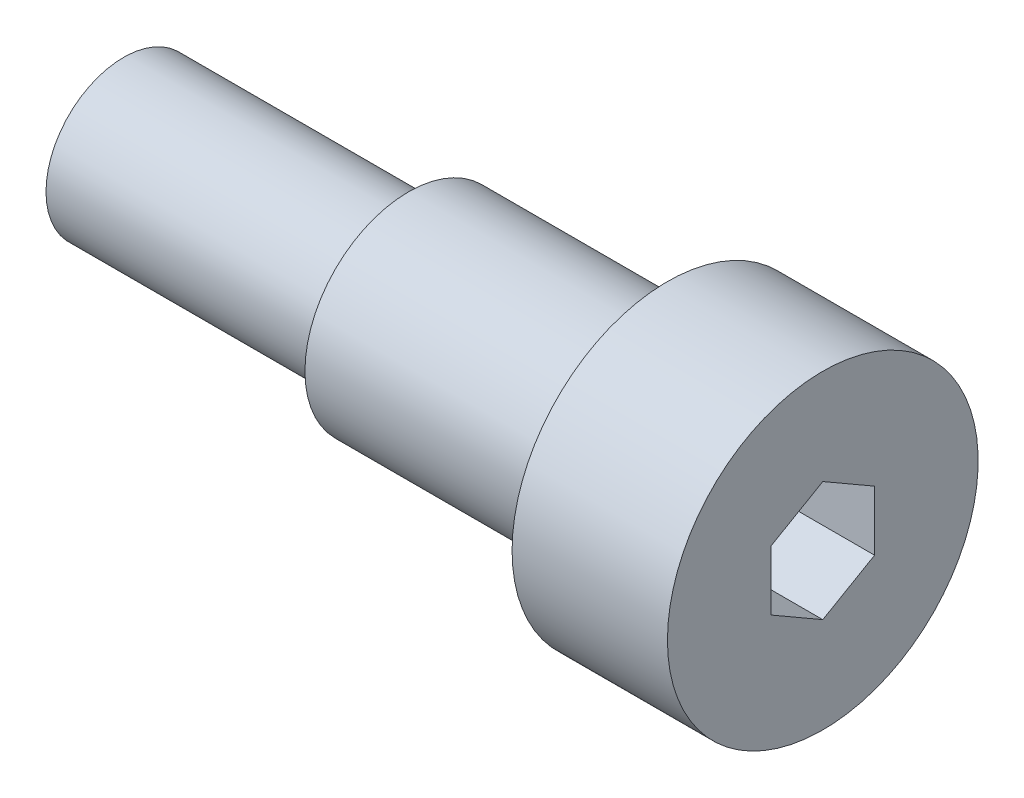
SolidWorks part; units mm, degrees
ref_plane "Front Plane" through (0, 0, 0) normal (0, 0, 1) x (1, 0, 0)
ref_plane "Top Plane" through (0, 0, 0) normal (0, 1, 0) x (1, 0, 0)
ref_plane "Right Plane" through (0, 0, 0) normal (1, 0, 0) x (0, 0, -1)
sketch "Sketch1" plane through (0, 0, 0) normal (0, 0, 1) x (1, 0, 0)
  line L0 (0, 0) -> (104.2442, 0) construction
  line L1 (16, 0) -> (16, 6)
  line L2 (16, 6) -> (10, 6)
  line L3 (10, 6) -> (10, 4)
  line L4 (10, 4) -> (0, 4)
  line L5 (0, 4) -> (0, 3)
  line L6 (0, 3) -> (-11, 3)
  line L7 (-11, 3) -> (-11, 0)
  line L8 (-11, 0) -> (16, 0)
  dimension "D_THREAD" = 6
  dimension "L_THREAD" = 11
  dimension "D_SHANK" = 8
  dimension "L_SHANK" = 10
  dimension "L_HEAD" = 6
  dimension "D_HEAD" = 12
revolve "Revolve1" add sketch "Sketch1" angle 360 about L0
cosmetic thread "Cosmetic Thread1" parameters "D2"=5
sketch "Sketch2" plane through (16, 0, 0) normal (1, 0, 0) x (0, 0, -1)
  line L1 (0, 2.3094) -> (-2, 1.1547)
  line L2 (-2, 1.1547) -> (-2, -1.1547)
  line L3 (-2, -1.1547) -> (0, -2.3094)
  line L4 (0, -2.3094) -> (2, -1.1547)
  line L5 (2, -1.1547) -> (2, 1.1547)
  line L6 (2, 1.1547) -> (0, 2.3094)
  circle A0 centre (0, 0) radius 2 construction
  dimension "D1" = 4
extrude "Cut-Extrude1" cut sketch "Sketch2" against normal blind 4
